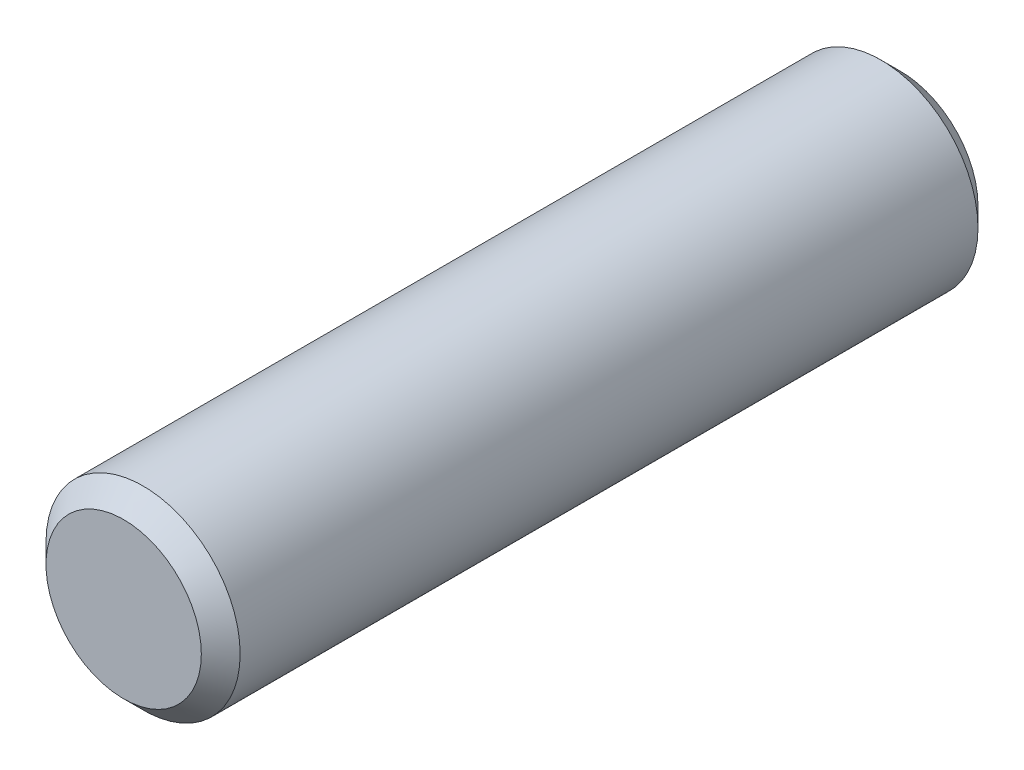
SolidWorks part; units mm, degrees
ref_plane "정면" through (0, 0, 0) normal (0, 0, 1) x (1, 0, 0)
ref_plane "윗면" through (0, 0, 0) normal (0, 1, 0) x (1, 0, 0)
ref_plane "우측면" through (0, 0, 0) normal (1, 0, 0) x (0, 0, -1)
sketch "스케치1" plane through (0, 0, 0) normal (0, 0, 1) x (1, 0, 0)
  circle A0 centre (0, 0) radius 3.5
  dimension "D1" = 7
extrude "보스-돌출1" add sketch "스케치1" along normal mid plane 28
chamfer "모따기1" distance 0.7 angle 45 2 edges at (3.5, 0, -14) (3.5, 0, 14)
